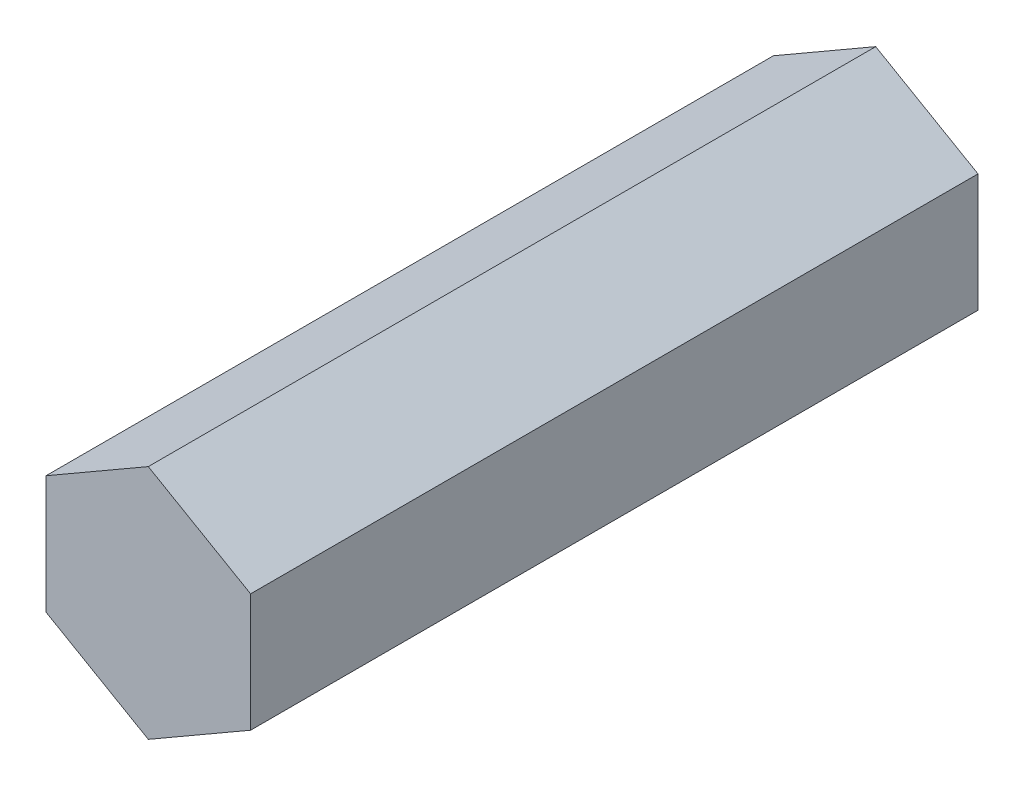
SolidWorks part; units mm, degrees
ref_plane "Front Plane" through (0, 0, 0) normal (0, 0, 1) x (1, 0, 0)
ref_plane "Top Plane" through (0, 0, 0) normal (0, 1, 0) x (1, 0, 0)
ref_plane "Right Plane" through (0, 0, 0) normal (1, 0, 0) x (0, 0, -1)
sketch "Sketch1" plane through (0, 0, 0) normal (0, 0, 1) x (1, 0, 0)
  line L0 (-7.1438, 0) -> (7.1438, 0) construction
  line L9 (0, 8.2489) -> (-7.1437, 4.1244) construction
  line L10 (-7.1437, 4.1244) -> (-7.1437, -4.1244) construction
  line L11 (-7.1437, -4.1244) -> (0, -8.2489) construction
  line L12 (0, -8.2489) -> (7.1437, -4.1244) construction
  line L13 (7.1437, -4.1244) -> (7.1437, 4.1244) construction
  line L14 (7.1437, 4.1244) -> (0, 8.2489) construction
  circle A3 centre (0, 0) radius 7.1437 construction
  point P4 (0, 0)
  dimension "Width" = 14.2875
sketch "Sketch2" plane through (0, 0, 0) normal (1, 0, 0) x (0, 0, -1)
  line L0 (63.5, 8.2489) -> (-63.5, 8.2489) construction
  point P3 (-47.0694, 8.2489)
  point P4 (0, 8.2489)
  point P5 (47.0694, 8.2489)
  dimension "Length" = 127
  dimension "D1" = 16.4306
  dimension "D2" = 16.4306
sketch "Sketch3" plane through (0, 0, 0) normal (0, 0, 1) x (1, 0, 0)
  line L1 (0, 8.2489) -> (7.1437, 4.1244)
  line L2 (7.1437, 4.1244) -> (7.1437, -4.1244)
  line L3 (7.1437, -4.1244) -> (0, -8.2489)
  line L4 (0, -8.2489) -> (-7.1437, -4.1244)
  line L5 (-7.1437, -4.1244) -> (-7.1437, 4.1244)
  line L6 (-7.1437, 4.1244) -> (0, 8.2489)
extrude "Boss-Extrude1" add sketch "Sketch3" along normal mid plane 50.8
equation "\"D1@Boss-Extrude1\"=\"A\""
equation "\"D1@Sketch2\" = \"Width@Sketch1\" * 1.15"
equation "\"D2@Sketch2\"=\"D1@Sketch2\""
equation "\"A\"= 2"
